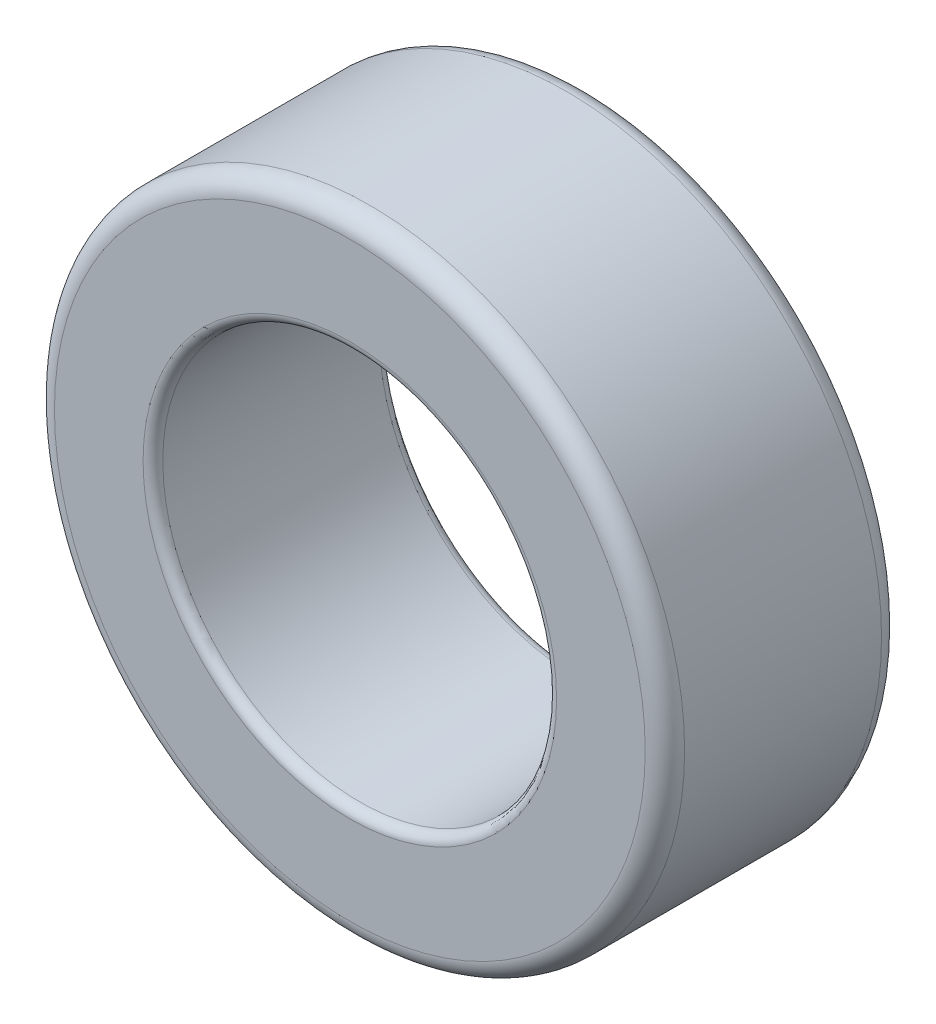
SolidWorks part; units mm, degrees
material "ABS PC"
ref_plane "前视基准面" through (0, 0, 0) normal (0, 0, 1) x (1, 0, 0)
ref_plane "上视基准面" through (0, 0, 0) normal (0, 1, 0) x (1, 0, 0)
ref_plane "右视基准面" through (0, 0, 0) normal (1, 0, 0) x (0, 0, -1)
sketch "草图1" plane through (0, 0, 0) normal (0, 0, 1) x (1, 0, 0)
  circle A0 centre (0, 0) radius 4
  circle A1 centre (0, 0) radius 10
  circle A2 centre (0, 0) radius 16
  circle A3 centre (0, 0) radius 5
  circle A4 centre (0, 0) radius 9
  dimension "D1" = 20
  dimension "D2" = 8
  dimension "D3" = 10
  dimension "D4" = 18
  dimension "D5" = 32
extrude "凸台-拉伸4" add sketch "草图1" along normal mid plane 12 contours A2 A1
fillet "圆角1" radius 1 2 edges at (16, 0, -6) (16, 0, 6)
fillet "圆角2" radius 0.5 2 edges at (10, 0, -6) (10, 0, 6)
